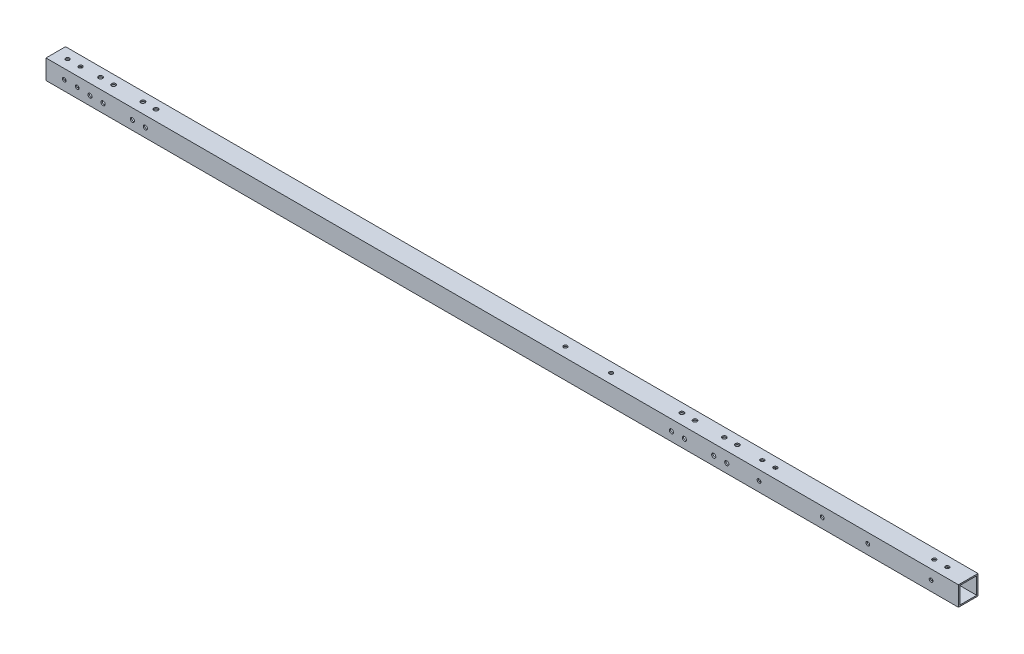
SolidWorks part; units mm, degrees
material "Thornel Mat VMA"
ref_plane "前视基准面" through (0, 0, 0) normal (0, 0, 1) x (1, 0, 0)
ref_plane "上视基准面" through (0, 0, 0) normal (0, 1, 0) x (1, 0, 0)
ref_plane "右视基准面" through (0, 0, 0) normal (1, 0, 0) x (0, 0, -1)
other "Configuration Table"
sketch "草图1" plane through (0, 0, 0) normal (1, 0, 0) x (0, 0, -1)
  line L0 (-6.5, -6.5) -> (-6.5, 6.5)
  line L1 (-7.5, -7.5) -> (7.5, -7.5)
  line L2 (-7.5, -7.5) -> (-7.5, 7.5)
  line L3 (-7.5, 7.5) -> (7.5, 7.5)
  line L4 (7.5, -7.5) -> (7.5, 7.5)
  line L5 (-7.5, -7.5) -> (7.5, 7.5) construction
  line L6 (-7.5, 7.5) -> (7.5, -7.5) construction
  line L7 (-6.5, 6.5) -> (6.5, 6.5)
  line L8 (6.5, -6.5) -> (6.5, 6.5)
  line L9 (-6.5, -6.5) -> (6.5, -6.5)
  point P0 (0, 0)
  dimension "D1" = 15
  dimension "D2" = 15
  dimension "D3" = 1
extrude "凸台-拉伸1" add sketch "草图1" along normal blind 700
sketch "草图3" plane through (0, 0, 7.5) normal (0, 0, 1) x (1, 0, 0)
  circle A0 centre (595.5, 0) radius 1.45 construction
  circle A1 centre (595.5, 0) radius 1.45
  circle A2 centre (24, 0) radius 1.45 construction
  circle A3 centre (14, 0) radius 1.45 construction
  circle A4 centre (76.25, -0.6213) radius 1.6 construction
  circle A5 centre (66.25, -0.6213) radius 1.6 construction
  circle A6 centre (43.75, -0.6213) radius 1.6 construction
  circle A7 centre (33.75, -0.6213) radius 1.6 construction
  circle A8 centre (522.25, -0.6213) radius 1.6 construction
  circle A9 centre (512.25, -0.6213) radius 1.6 construction
  circle A10 centre (489.75, -0.6213) radius 1.6 construction
  circle A11 centre (479.75, -0.6213) radius 1.6 construction
  circle A12 centre (630.5, 0) radius 1.45 construction
  circle A13 centre (24, 0) radius 1.45
  circle A14 centre (14, 0) radius 1.45
  circle A15 centre (76.25, -0.6213) radius 1.6
  circle A16 centre (66.25, -0.6213) radius 1.6
  circle A17 centre (43.75, -0.6213) radius 1.6
  circle A18 centre (33.75, -0.6213) radius 1.6
  circle A19 centre (522.25, -0.6213) radius 1.6
  circle A20 centre (512.25, -0.6213) radius 1.6
  circle A21 centre (489.75, -0.6213) radius 1.6
  circle A22 centre (479.75, -0.6213) radius 1.6
  circle A23 centre (630.5, 0) radius 1.45
  circle A24 centre (547, 0) radius 1.45 construction
  circle A25 centre (679, 0) radius 1.45 construction
  circle A26 centre (547, 0) radius 1.45
  circle A27 centre (679, 0) radius 1.45
extrude "切除-拉伸1" cut sketch "草图3" against normal through all
sketch "草图4" plane through (0, 7.5, 0) normal (0, 1, 0) x (1, 0, 0)
  circle A0 centre (9, 0) radius 1.45 construction
  circle A1 centre (19, 0) radius 1.45 construction
  circle A2 centre (19, 0) radius 1.45 construction
  circle A3 centre (33.75, 0.6213) radius 1.6 construction
  circle A4 centre (43.75, 0.6213) radius 1.6 construction
  circle A5 centre (66.25, 0.6213) radius 1.6 construction
  circle A6 centre (76.25, 0.6213) radius 1.6 construction
  circle A7 centre (391, 0) radius 1.45 construction
  circle A8 centre (426, 0) radius 1.45 construction
  circle A9 centre (479.75, 0.6213) radius 1.6 construction
  circle A10 centre (479.75, 0.6213) radius 1.6 construction
  circle A11 centre (489.75, 0.6213) radius 1.6 construction
  circle A12 centre (512.25, 0.6213) radius 1.6 construction
  circle A13 centre (522.25, 0.6213) radius 1.6 construction
  circle A14 centre (9, 0) radius 1.45
  circle A15 centre (19, 0) radius 1.45
  circle A16 centre (19, 0) radius 1.45
  circle A17 centre (33.75, 0.6213) radius 1.6
  circle A18 centre (43.75, 0.6213) radius 1.6
  circle A19 centre (66.25, 0.6213) radius 1.6
  circle A20 centre (76.25, 0.6213) radius 1.6
  circle A21 centre (391, 0) radius 1.45
  circle A22 centre (426, 0) radius 1.45
  circle A23 centre (479.75, 0.6213) radius 1.6
  circle A24 centre (479.75, 0.6213) radius 1.6
  circle A25 centre (489.75, 0.6213) radius 1.6
  circle A26 centre (512.25, 0.6213) radius 1.6
  circle A27 centre (522.25, 0.6213) radius 1.6
  circle A28 centre (684, 0) radius 1.45 construction
  circle A29 centre (674, 0) radius 1.45 construction
  circle A30 centre (552, 0) radius 1.45 construction
  circle A31 centre (542, 0) radius 1.45 construction
  circle A32 centre (684, 0) radius 1.45
  circle A33 centre (674, 0) radius 1.45
  circle A34 centre (552, 0) radius 1.45
  circle A35 centre (542, 0) radius 1.45
extrude "切除-拉伸2" cut sketch "草图4" against normal through all contours A14 | A17 | A18 | A20 | A19 | A22 | A21 | A26 | A25 | A23 | A27 | A34 | A33 | A32 | A15 | A35
